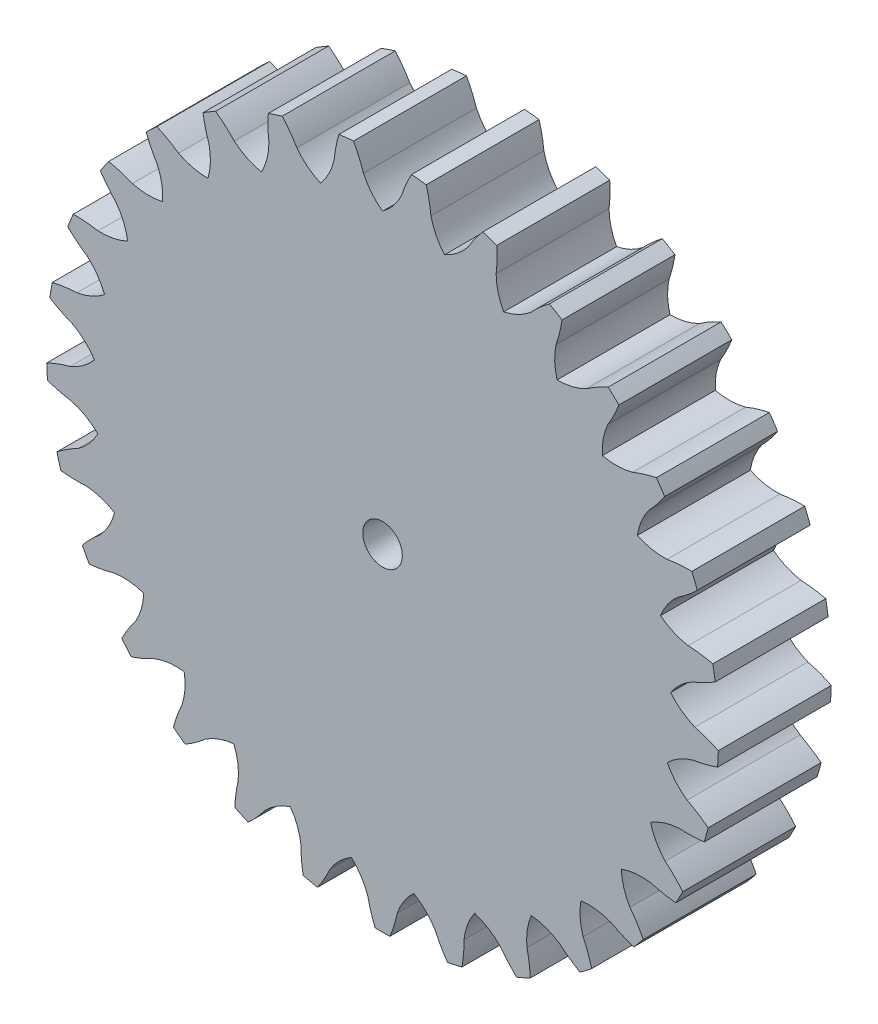
SolidWorks part; units mm, degrees
ref_plane "Front Plane" through (0, 0, 0) normal (0, 0, 1) x (1, 0, 0)
ref_plane "Top Plane" through (0, 0, 0) normal (0, 1, 0) x (1, 0, 0)
ref_plane "Right Plane" through (0, 0, 0) normal (1, 0, 0) x (0, 0, -1)
sketch "Sketch1" plane through (0, 0, 0) normal (0, 0, 1) x (1, 0, 0)
  line L1 (1.2374, -1.2374) -> (-1.2374, -1.2374) construction
  line L2 (1.2374, -1.2374) -> (1.2374, 1.2374) construction
  line L3 (1.2374, 1.2374) -> (-1.2374, 1.2374) construction
  line L4 (-1.2374, -1.2374) -> (-1.2374, 1.2374) construction
  line L5 (1.2374, -1.2374) -> (-1.2374, 1.2374) construction
  line L6 (1.2374, 1.2374) -> (-1.2374, -1.2374) construction
  circle A0 centre (0, 0) radius 29.75
  circle A1 centre (0, 0) radius 1.75
  dimension "D1" = 59.5
  dimension "D2" = 3.5
extrude "Boss-Extrude1" add sketch "Sketch1" along normal blind 10
sketch "Sketch2" plane through (0, 0, 0) normal (0, 0, 1) x (1, 0, 0)
  line L0 (0, 0) -> (0, 36.6661) construction
  arc A25 (0, 25.5436) -> (-1.6909, 27.6123) centre (3.2409, 29.9179) cw
  arc A26 (-1.6909, 27.6123) -> (-6.9218, 34.1) centre (-12.7926, 24.0138) ccw
  arc A27 (-6.9218, 34.1) -> (0, 36.6661) centre (0.5436, 24.5815) cw
  arc A28 (6.9218, 34.1) -> (0, 36.6661) centre (-0.5436, 24.5815) ccw
  arc A29 (1.6909, 27.6123) -> (6.9218, 34.1) centre (12.7926, 24.0138) cw
  arc A30 (0, 25.5436) -> (1.6909, 27.6123) centre (-3.2409, 29.9179) ccw
extrude "Cut-Extrude1" cut sketch "Sketch2" along normal through all
pattern_circular "CirPattern1" count 29 over 360 about axis through (0, 0, 0) along (0, 0, 1) of "Cut-Extrude1"
sketch "Sketch3" plane through (0, 0, 0) normal (0, 0, 1) x (1, 0, 0)
  circle A0 centre (0, 0) radius 29.75
  dimension "D1" = 59.5
